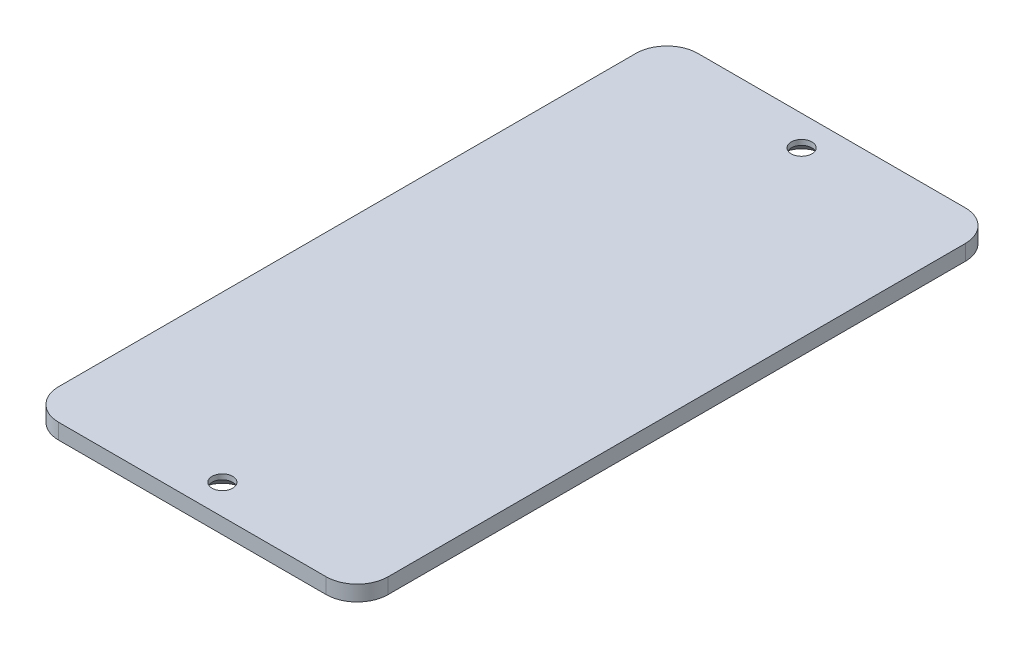
SolidWorks part; units mm, degrees
ref_plane "Front Plane" through (0, 0, 0) normal (0, 0, 1) x (1, 0, 0)
ref_plane "Top Plane" through (0, 0, 0) normal (0, 1, 0) x (1, 0, 0)
ref_plane "Right Plane" through (0, 0, 0) normal (1, 0, 0) x (0, 0, -1)
sketch "Sketch1" plane through (0, 0, 0) normal (0, 1, 0) x (1, 0, 0)
  line L1 (-31.9, 61.9) -> (31.9, 61.9)
  line L2 (-31.9, 61.9) -> (-31.9, -61.9)
  line L3 (-31.9, -61.9) -> (31.9, -61.9)
  line L4 (31.9, 61.9) -> (31.9, -61.9)
  line L5 (-31.9, 61.9) -> (31.9, -61.9) construction
  line L6 (-31.9, -61.9) -> (31.9, 61.9) construction
  point P0 (0, 0)
  dimension "D1" = 63.8
  dimension "D2" = 123.8
extrude "Boss-Extrude1" add sketch "Sketch1" along normal blind 3
sketch "Sketch2" plane through (0, 3, 0) normal (0, 1, 0) x (1, 0, 0)
  line L0 (-31.9, -61.9) -> (31.9, -61.9) construction
  circle A0 centre (0, -56.1) radius 2
  dimension "D2" = 4
  dimension "D1" = 5.8
extrude "Cut-Extrude1" cut sketch "Sketch2" against normal through all
hole_wizard "CSK for M4 Hex Socket Countersunk Head Screw1" positions "3DSketch1" profile "Sketch3" countersink size "M4" standard "DIN" end condition through all
sketch3d "3DSketch1"
  line L0 (0, 0, 56.1) -> (0, 3, 56.1) construction
  point P0 (0, 0, 56.1)
sketch "Sketch3" plane through (0, 0, 56.1) normal (1, 0, 0) x (0, 0, -1)
  line L0 (0, 0) -> (0, 3)
  line L1 (0, 3) -> (2, 3)
  line L2 (2, 3) -> (2, 2)
  line L3 (2, 2) -> (4, 0)
  line L5 (4, 0) -> (0, 0)
  line L6 (-2, 2) -> (-4, 0) construction
  line L11 (0, -6.35) -> (0, 107.95) construction
  dimension "Thru Hole Dia." = 4
  dimension "Thru Hole Depth" = 3
  dimension "Near C'Sink Dia." = 8
  dimension "Near C'Sink Angle" = 90
mirror "Mirror1" about plane through (0, 0, 0) normal (0, 0, 1) of "Cut-Extrude1", "CSK for M4 Hex Socket Countersunk Head Screw1"
fillet "Fillet1" radius 6 4 edges at (31.9, 1.5, -61.9) (31.9, 1.5, 61.9) (-31.9, 1.5, 61.9) (-31.9, 1.5, -61.9)
